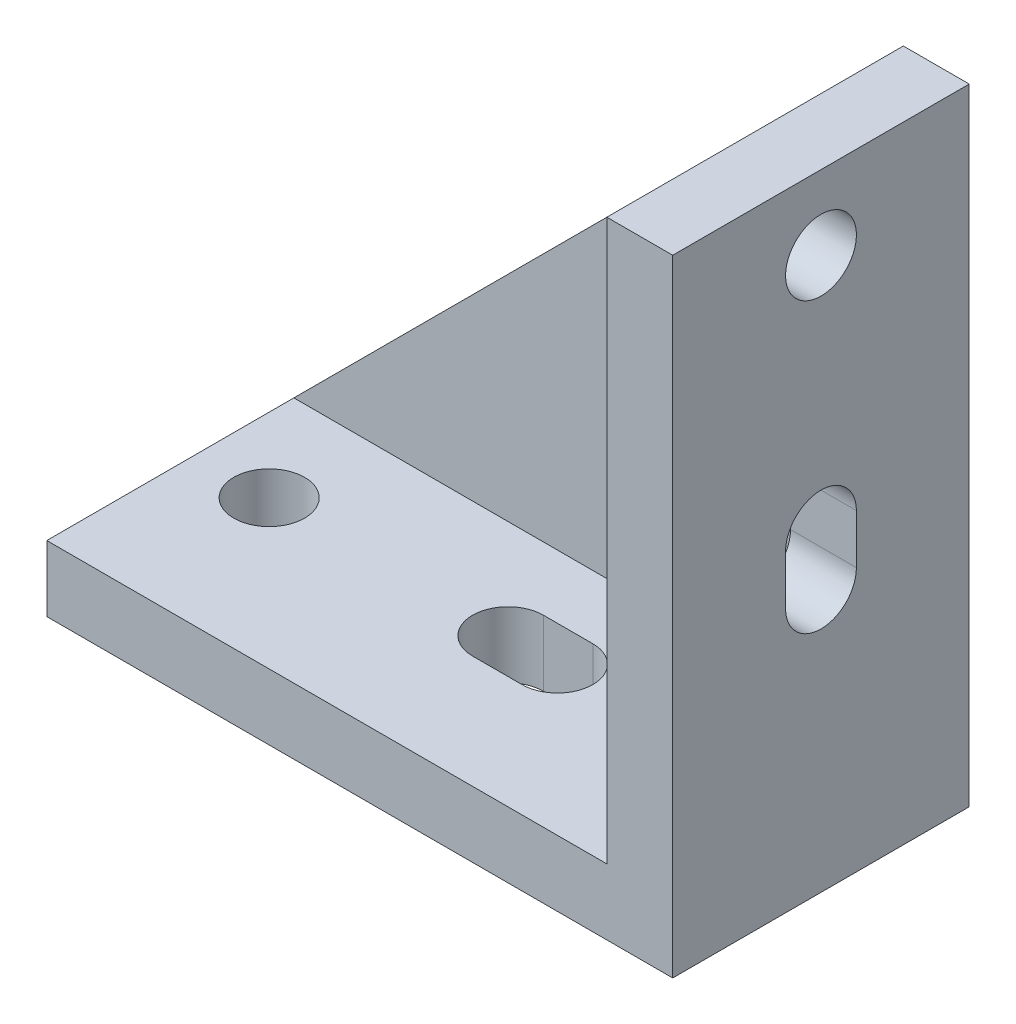
SolidWorks part; units mm, degrees
ref_plane "前视基准面" through (0, 0, 0) normal (0, 0, 1) x (1, 0, 0)
ref_plane "上视基准面" through (0, 0, 0) normal (0, 1, 0) x (1, 0, 0)
ref_plane "右视基准面" through (0, 0, 0) normal (1, 0, 0) x (0, 0, -1)
sketch "草图1" plane through (0, 0, 0) normal (0, 0, 1) x (1, 0, 0)
  line B0 (-38, 0) -> (0, 0)
  line B1 (0, 0) -> (0, 38)
  line B2 (-38, 4) -> (-4, 4)
  line B3 (-4, 4) -> (-4, 38)
  line B4 (-4, 38) -> (0, 38)
  line B5 (-38, 4) -> (-38, 0)
sketch_block_instance "A$C31CB38A4-1"
sketch_block "A$C31CB38A4"
extrude "凸台-拉伸1" add sketch "草图1" along normal mid plane 18
sketch "草图3" plane through (0, 0, -9) normal (0, 0, -1) x (-1, 0, 0)
  line L0 (38, 4) -> (4, 38)
  line L1 (4, 38) -> (4, 4) construction
  line L2 (0, 38) -> (4, 38) construction
  line L3 (4, 38) -> (4, 4)
  line L4 (4, 4) -> (38, 4)
extrude "凸台-拉伸2" add sketch "草图3" against normal blind 3
sketch "草图4" plane through (0, 4, 0) normal (0, 1, 0) x (1, 0, 0)
  line L0 (-16, 0) -> (-19, 0) construction
  line L1 (-16, -2.15) -> (-19, -2.15)
  line L2 (-16, 2.15) -> (-19, 2.15)
  line L3 (-38, 9) -> (-4, 9) construction
  line L4 (0, -9) -> (0, 9) construction
  arc A0 (-16, -2.15) -> (-16, 2.15) centre (-16, 0) ccw
  arc A1 (-19, 2.15) -> (-19, -2.15) centre (-19, 0) ccw
  circle A2 centre (-33.5, 0) radius 2.15
  point P2 (-17.5, 0)
  dimension "D3" = 16
  dimension "D5" = 4.3
  dimension "D6" = 14.5
  dimension "D1" = 9
  dimension "D2" = 2.15
  dimension "D4" = 3
extrude "切除-拉伸1" cut sketch "草图4" against normal through all
ref_plane "基准面2" through (0, 0, 0) normal (-0.7071, -0.7071, 0) x (-0.7071, 0.7071, 0)
mirror "镜向1" about plane through (0, 0, 0) normal (-0.7071, -0.7071, 0) of "切除-拉伸1"
